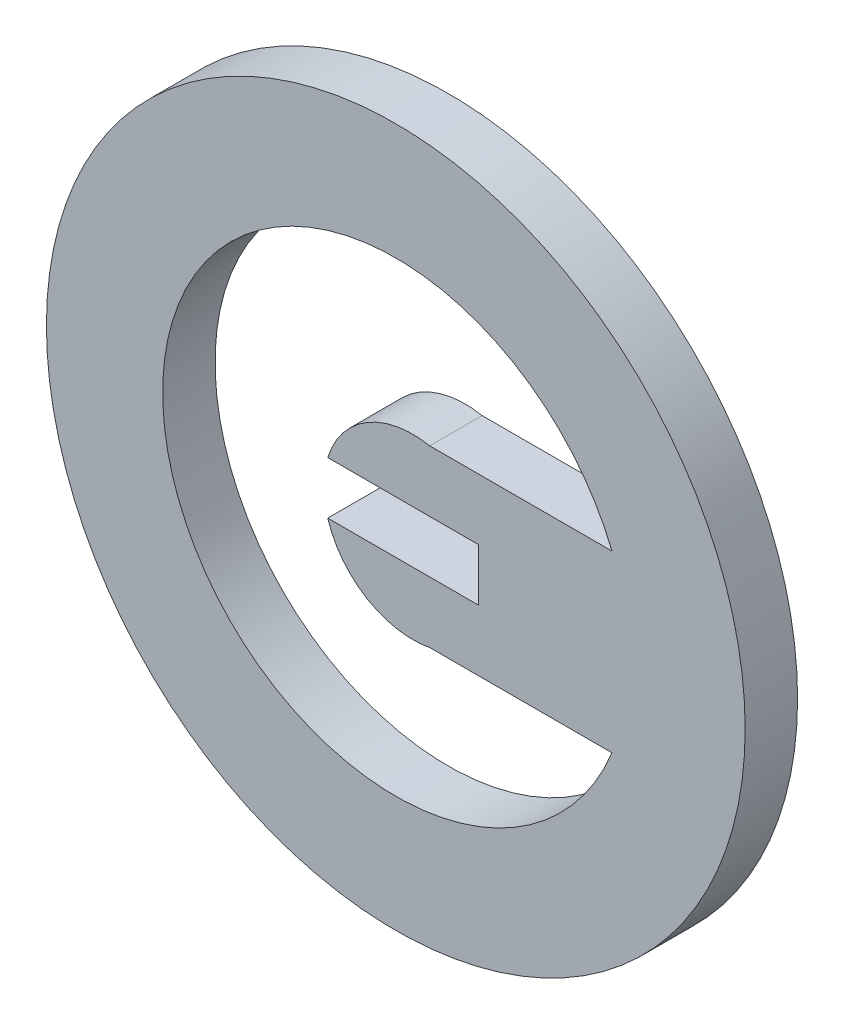
SolidWorks part; units mm, degrees
ref_plane "Front" through (0, 0, 0) normal (0, 0, 1) x (1, 0, 0)
ref_plane "Top" through (0, 0, 0) normal (0, 1, 0) x (1, 0, 0)
ref_plane "Right" through (0, 0, 0) normal (1, 0, 0) x (0, 0, -1)
sketch "Sketch1" plane through (0, 0, 0) normal (0, 0, 1) x (1, 0, 0)
  line L1 (1.9442, 5) -> (12.3734, 5)
  line L2 (1.9442, -5) -> (12.3734, -5)
  line L3 (-3.8956, 1.5) -> (4.7362, 1.5)
  line L4 (-3.8956, -1.5) -> (4.7362, -1.5)
  line L5 (4.7362, 1.5) -> (4.7362, -1.5)
  circle A0 centre (0, 0) radius 20
  arc A1 (12.3734, 5) -> (12.3734, -5) centre (0, 0) ccw
  arc A2 (1.9442, 5) -> (-3.8956, 1.5) centre (0.9721, 0) ccw
  arc A3 (-3.8956, -1.5) -> (1.9442, -5) centre (0.9721, 0) ccw
extrude "Base-Extrude" add sketch "Sketch1" along normal blind 3
